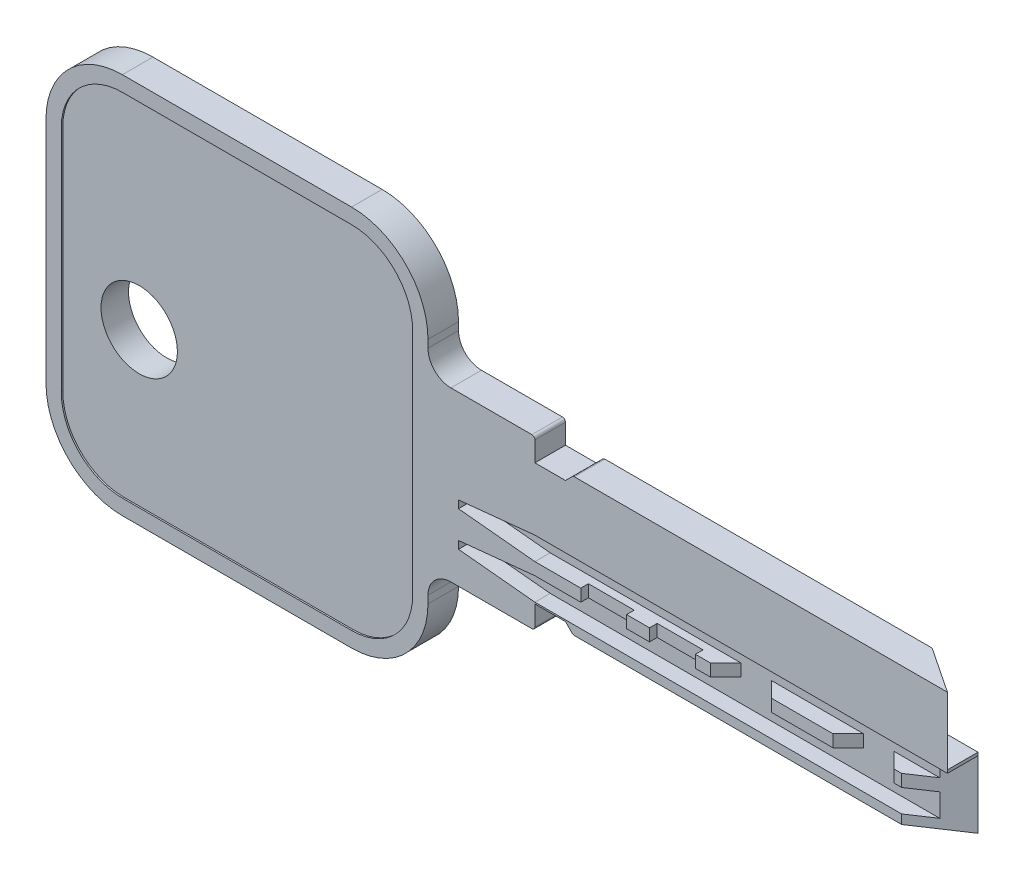
SolidWorks part; units mm, degrees
material "Alloy Steel"
ref_plane "Front Plane" through (0, 0, 0) normal (0, 0, 1) x (1, 0, 0)
ref_plane "Top Plane" through (0, 0, 0) normal (0, 1, 0) x (1, 0, 0)
ref_plane "Right Plane" through (0, 0, 0) normal (1, 0, 0) x (0, 0, -1)
sketch "Sketch1" plane through (0, 0, 0) normal (0, 0, 1) x (1, 0, 0)
  line L1 (-7.5, 12.5) -> (7.5, 12.5)
  line L2 (-12.5, 7.5) -> (-12.5, -7.5)
  line L3 (-7.5, -12.5) -> (7.5, -12.5)
  line L4 (12.5, 7.5) -> (12.5, -7.5) construction
  line L5 (-12.5, 12.5) -> (12.5, -12.5) construction
  line L6 (-12.5, -12.5) -> (12.5, 12.5) construction
  line L7 (12.5, 0) -> (46.5, 0) construction
  line L8 (12.5, 7.5) -> (12.5, 7)
  line L9 (14, 5.5) -> (46.5, 5.5)
  line L10 (12.5, 5.5) -> (12.5, -5.5) construction
  line L11 (14, -5.5) -> (46.5, -5.5)
  line L12 (46.5, 5.5) -> (46.5, -5.5)
  line L13 (12.5, -7.5) -> (12.5, -7)
  arc A0 (7.5, -12.5) -> (12.5, -7.5) centre (7.5, -7.5) ccw
  arc A1 (-12.5, -7.5) -> (-7.5, -12.5) centre (-7.5, -7.5) ccw
  arc A2 (7.5, 12.5) -> (12.5, 7.5) centre (7.5, 7.5) cw
  arc A3 (-7.5, 12.5) -> (-12.5, 7.5) centre (-7.5, 7.5) ccw
  circle A4 centre (-6.5, -1.5) radius 2.5
  arc A5 (12.5, -7) -> (14, -5.5) centre (14, -7) cw
  arc A6 (14, 5.5) -> (12.5, 7) centre (14, 7) cw
  point P0 (0, 0)
  dimension "D2" = 5
  dimension "D4" = 5
  dimension "D7" = 1.5
  dimension "D1" = 25
  dimension "D3" = 6
  dimension "D5" = 11
  dimension "D6" = 34
  dimension "D8" = 11
extrude "Boss-Extrude1" add sketch "Sketch1" along normal mid plane 2
sketch "Sketch2" plane through (0, 0, 1) normal (0, 0, 1) x (1, 0, 0)
  line L0 (12.5, 7) -> (12.5, 7.5) construction
  line L1 (7.5, 12.5) -> (-7.5, 12.5) construction
  line L2 (-12.5, 7.5) -> (-12.5, -7.5) construction
  line L3 (-7.5, -12.5) -> (7.5, -12.5) construction
  line L4 (12.5, -7.5) -> (12.5, -7) construction
  line L5 (12.5, 7) -> (12.5, 7.5) construction
  line L6 (7.5, 12.5) -> (-7.5, 12.5) construction
  line L7 (-12.5, 7.5) -> (-12.5, -7.5) construction
  line L8 (-7.5, -12.5) -> (7.5, -12.5) construction
  line L9 (12.5, -7.5) -> (12.5, -7) construction
  line L10 (12.5, 7) -> (12.5, -7) construction
  line L11 (11.5, 7) -> (11.5, 7.5)
  line L12 (7.5, 11.5) -> (-7.5, 11.5)
  line L13 (-11.5, 7.5) -> (-11.5, -7.5)
  line L14 (-7.5, -11.5) -> (7.5, -11.5)
  line L15 (11.5, -7.5) -> (11.5, -7)
  line L16 (11.5, 7) -> (11.5, -7)
  arc A0 (12.5, 7.5) -> (7.5, 12.5) centre (7.5, 7.5) ccw construction
  arc A1 (-7.5, 12.5) -> (-12.5, 7.5) centre (-7.5, 7.5) ccw construction
  arc A2 (-12.5, -7.5) -> (-7.5, -12.5) centre (-7.5, -7.5) ccw construction
  arc A3 (7.5, -12.5) -> (12.5, -7.5) centre (7.5, -7.5) ccw construction
  arc A4 (12.5, 7.5) -> (7.5, 12.5) centre (7.5, 7.5) ccw construction
  arc A5 (-7.5, 12.5) -> (-12.5, 7.5) centre (-7.5, 7.5) ccw construction
  arc A6 (-12.5, -7.5) -> (-7.5, -12.5) centre (-7.5, -7.5) ccw construction
  arc A7 (7.5, -12.5) -> (12.5, -7.5) centre (7.5, -7.5) ccw construction
  arc A8 (11.5, 7.5) -> (7.5, 11.5) centre (7.5, 7.5) ccw
  arc A9 (-7.5, 11.5) -> (-11.5, 7.5) centre (-7.5, 7.5) ccw
  arc A10 (-11.5, -7.5) -> (-7.5, -11.5) centre (-7.5, -7.5) ccw
  arc A11 (7.5, -11.5) -> (11.5, -7.5) centre (7.5, -7.5) ccw
  dimension "D1" = 1
extrude "Cut-Extrude2" cut sketch "Sketch2" against normal blind 0.1
mirror "Mirror1" about plane through (0, 0, 0) normal (0, 0, 1) of "Cut-Extrude2"
sketch "Sketch3" plane through (0, 0, 1) normal (0, 0, 1) x (1, 0, 0)
  line L0 (19.5, 5.5) -> (19.5, 4)
  line L1 (46.5, 5.5) -> (14, 5.5) construction
  line L2 (19.5, 4) -> (21.5, 4)
  line L3 (21.5, 4) -> (22, 4.5)
  line L4 (22, 4.5) -> (46.5, 4.5)
  line L5 (46.5, -5.5) -> (46.5, 5.5) construction
  line L6 (46.5, 4.5) -> (46.5, 5.5)
  line L7 (46.5, 5.5) -> (19.5, 5.5)
  line L8 (12.5, 7) -> (12.5, 7.5) construction
  dimension "D1" = 1.5
  dimension "D2" = 7
  dimension "D3" = 1
  dimension "D4" = 2
  dimension "D5" = 2.5
extrude "Cut-Extrude3" cut sketch "Sketch3" along direction (0, 0, 1) on the side against the normal up to next (2 mm away)
fillet "Fillet1" radius 0.2 2 edges at (22, 4.5, 0) (19.5, 5.5, 0)
mirror "Mirror2" about plane through (0, 0, 0) normal (0, 1, 0) of "Cut-Extrude3", "Fillet1"
sketch "Sketch4" plane through (0, 0, 1) normal (0, 0, 1) x (1, 0, 0)
  line L0 (46.5, -0.1) -> (19.5, -0.1)
  line L1 (46.5, -4.5) -> (46.5, 4.5) construction
  line L2 (19.5, -0.1) -> (14.5, -0.6)
  line L3 (14.5, -0.6) -> (14.5, -1.1)
  line L4 (14.5, -1.1) -> (19.5, -1.6)
  line L5 (19.5, -1.6) -> (46.5, -1.6)
  line L6 (46.5, -1.6) -> (46.5, -0.1)
  line L7 (14.5, -0.85) -> (46.5, -0.85) construction
  line L9 (22.0828, -4.5) -> (46.5, -4.5) construction
  dimension "D1" = 5
  dimension "D2" = 1.5
  dimension "D3" = 0.5
  dimension "D4" = 32
  dimension "D5" = 2.9
extrude "Cut-Extrude4" cut sketch "Sketch4" against normal blind 1
pattern_linear "LPattern1" count 2 spacing 2.3 along (0, -1, 0) of "Cut-Extrude4"
sketch "Sketch5" plane through (0, 0, 1) normal (0, 0, 1) x (1, 0, 0)
  line L0 (19.5, -1.6) -> (46.5, -1.6) construction
  line L1 (22.5, -1.6) -> (25.5, -1.6)
  line L2 (22.5, -1.6) -> (22.5, -2.4)
  line L3 (22.5, -2.4) -> (25.5, -2.4)
  line L4 (25.5, -1.6) -> (25.5, -2.4)
  line L5 (46.5, -2.4) -> (19.5, -2.4) construction
  line L6 (19.5, -1.6) -> (46.5, -1.6) construction
  line L7 (27, -1.6) -> (30, -1.6)
  line L8 (27, -1.6) -> (27, -2.4)
  line L9 (27, -2.4) -> (30, -2.4)
  line L10 (30, -1.6) -> (30, -2.4)
  line L11 (46.5, -2.4) -> (19.5, -2.4) construction
  line L12 (12.5, 7) -> (12.5, 7.5) construction
  dimension "D1" = 3
  dimension "D2" = 1.5
  dimension "D3" = 10
extrude "Cut-Extrude5" cut sketch "Sketch5" against normal blind 0.5
sketch "Sketch6" plane through (0, -2.4, 0) normal (0, -1, 0) x (1, 0, 0)
  line L0 (31, 1) -> (32, 0)
  line L1 (22.0828, 1) -> (46.5, 1) construction
  line L2 (32, 0) -> (34, 0)
  line L3 (34, 0) -> (35, 1)
  line L4 (35, 1) -> (31, 1)
  line L5 (39, 1) -> (40, 0)
  line L6 (40, 0) -> (42, 0)
  line L7 (42, 0) -> (43, 1)
  line L8 (43, 1) -> (39, 1)
  line L9 (33, 0) -> (33, 1) construction
  line L10 (41, 0) -> (41, 1) construction
  line L11 (46.5, -1) -> (46.5, 1) construction
  line M15 (19.5, 0) -> (46.5, 0)
  line M17 (46.5, 1) -> (30, 1)
  dimension "D1" = 4
  dimension "D2" = 2
  dimension "D3" = 4
  dimension "D4" = 3.5
extrude "Cut-Extrude6" cut sketch "Sketch6" against normal up to surface (0.8 mm away) contours L3 L0 M15 M17 | L7 L5 M15 M17 up to face at (28.5, -1.6, 0.6667)
sketch "Sketch7" plane through (0, -4.5, 0) normal (0, -1, 0) x (1, 0, 0)
  line L0 (46.5, -1) -> (43.5, 1)
  line L1 (22.0828, 1) -> (46.5, 1) construction
  line L2 (43.5, 1) -> (46.5, 1)
  line L3 (46.5, 1) -> (46.5, -1)
  dimension "D1" = 3
extrude "Cut-Extrude7" cut sketch "Sketch7" against normal up to surface (4.4 mm away) up to face at (33, -0.1, 0.5)
sketch "Sketch8" plane through (0, 0, -1) normal (0, 0, -1) x (-1, 0, 0)
  line L0 (-46.5, 0.1) -> (-19.5, 0.1)
  line L1 (-46.5, -4.5) -> (-46.5, -0.1) construction
  line L2 (-19.5, 0.1) -> (-14.5, 0.6)
  line L3 (-14.5, 0.6) -> (-14.5, 1.1)
  line L4 (-14.5, 1.1) -> (-19.5, 1.6)
  line L5 (-19.5, 1.6) -> (-46.5, 1.6)
  line L6 (-46.5, -0.1) -> (-46.5, 4.5) construction
  line L7 (-46.5, 1.6) -> (-46.5, 0.1)
  line L8 (-46.5, 0.85) -> (-14.5, 0.85) construction
  line L9 (-46.5, 4.5) -> (-22.0828, 4.5) construction
  dimension "D1" = 32
  dimension "D2" = 0.5
  dimension "D3" = 1.5
  dimension "D4" = 5
  dimension "D5" = 2.9
extrude "Cut-Extrude8" cut sketch "Sketch8" against normal blind 1
pattern_linear "LPattern2" count 2 spacing 2.3 along (0, 1, 0) of "Cut-Extrude8"
sketch "Sketch9" plane through (0, 0, -1) normal (0, 0, -1) x (-1, 0, 0)
  line L0 (-46.5, 2.4) -> (-19.5, 2.4) construction
  line L1 (-21.5, 2.4) -> (-24.5, 2.4)
  line L2 (-21.5, 2.4) -> (-21.5, 1.6)
  line L3 (-21.5, 1.6) -> (-24.5, 1.6)
  line L4 (-24.5, 2.4) -> (-24.5, 1.6)
  line L5 (-19.5, 1.6) -> (-46.5, 1.6) construction
  line L6 (-46.5, 2.4) -> (-19.5, 2.4) construction
  line L7 (-26, 2.4) -> (-29, 2.4)
  line L8 (-26, 2.4) -> (-26, 1.6)
  line L9 (-26, 1.6) -> (-29, 1.6)
  line L10 (-29, 2.4) -> (-29, 1.6)
  line L11 (-19.5, 1.6) -> (-46.5, 1.6) construction
  line L12 (-11.5, -7.5) -> (-11.5, 7.5) construction
  dimension "D1" = 3
  dimension "D2" = 10
  dimension "D3" = 1.5
extrude "Cut-Extrude9" cut sketch "Sketch9" against normal blind 0.5
sketch "Sketch10" plane through (0, 2.4, 0) normal (0, 1, 0) x (1, 0, 0)
  line L0 (31, 1) -> (32, 0)
  line L1 (46.5, 1) -> (22.0828, 1) construction
  line L2 (32, 0) -> (34, 0)
  line L3 (34, 0) -> (35, 1)
  line L4 (35, 1) -> (31, 1)
  line L5 (39, 1) -> (40, 0)
  line L6 (40, 0) -> (42, 0)
  line L7 (42, 0) -> (43, 1)
  line L8 (43, 1) -> (39, 1)
  line L9 (33, 0) -> (33, 1) construction
  line L10 (41, 0) -> (41, 1) construction
  line L11 (46.5, 1) -> (46.5, -1) construction
  dimension "D1" = 4
  dimension "D2" = 2
  dimension "D3" = 4
  dimension "D4" = 3.5
extrude "Cut-Extrude10" cut sketch "Sketch10" against normal up to surface (0.8 mm away) up to face at (27.8333, 1.6, -0.6667)
sketch "Sketch11" plane through (0, 4.5, 0) normal (0, 1, 0) x (1, 0, 0)
  line L0 (46.5, -1) -> (43.5, 1)
  line L1 (46.5, 1) -> (22.0828, 1) construction
  line L2 (43.5, 1) -> (46.5, 1)
  line L3 (46.5, 1) -> (46.5, -1)
  dimension "D1" = 3
extrude "Cut-Extrude11" cut sketch "Sketch11" against normal up to surface (4.4 mm away) up to face at (33, 0.1, -0.5)
